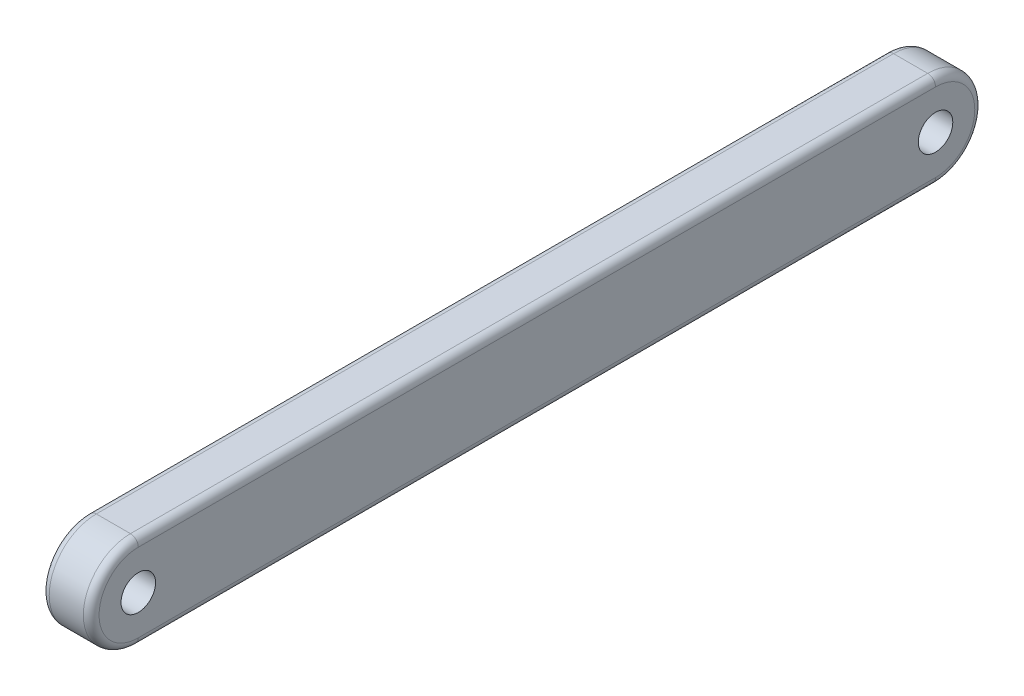
SolidWorks part; units mm, degrees
ref_plane "Front Plane" through (0, 0, 0) normal (0, 0, 1) x (1, 0, 0)
ref_plane "Top Plane" through (0, 0, 0) normal (0, 1, 0) x (1, 0, 0)
ref_plane "Right Plane" through (0, 0, 0) normal (1, 0, 0) x (0, 0, -1)
sketch "Sketch1" plane through (0, 0, 0) normal (1, 0, 0) x (0, 0, -1)
  line L0 (0, 0) -> (101.6, 0) construction
  line L1 (0, 6) -> (101.6, 6)
  line L2 (0, -6) -> (101.6, -6)
  arc A0 (0, 6) -> (0, -6) centre (0, 0) ccw
  arc A1 (101.6, -6) -> (101.6, 6) centre (101.6, 0) ccw
  circle A2 centre (0, 0) radius 2.2
  circle A3 centre (101.6, 0) radius 2.2
  point P4 (50.8, 0)
  dimension "D2" = 6
  dimension "D3" = 4.4
  dimension "D4" = 4.4
  dimension "D1" = 101.6
extrude "Boss-Extrude1" add sketch "Sketch1" along normal blind 6.35
fillet "Fillet1" radius 1 8 edges at (0, 0, -107.6) (0, -6, -50.8) (0, 0, 6) (6.35, 0, -107.6) (6.35, -6, -50.8) (6.35, 0, 6) (0, 6, -50.8) (6.35, 6, -50.8)
